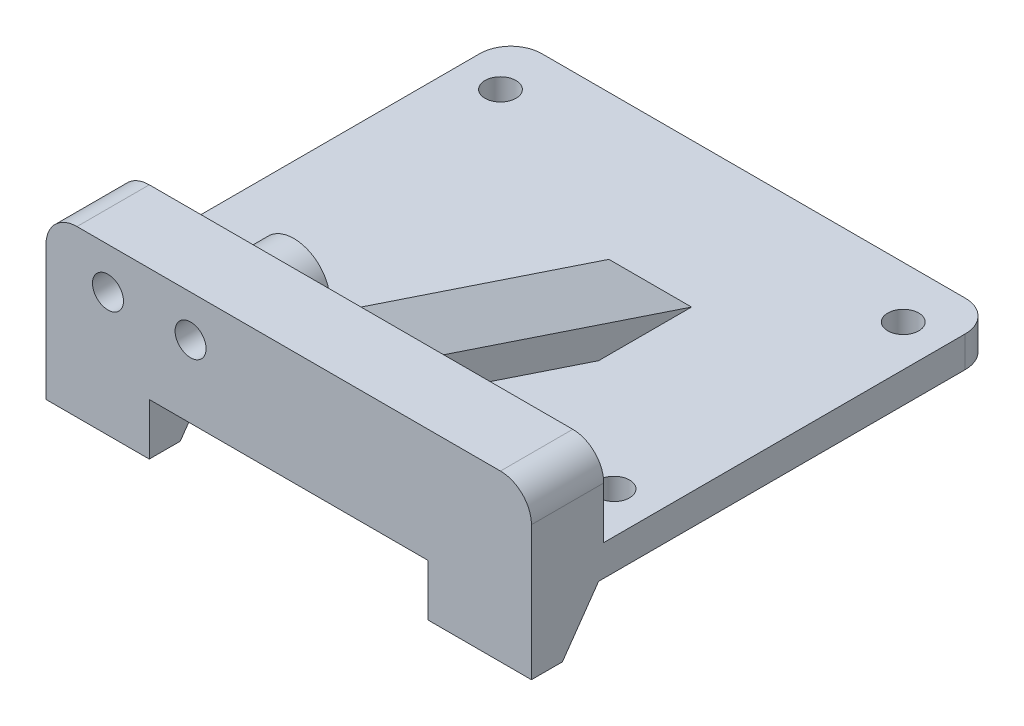
SolidWorks part; units mm, degrees
material "聚脂树脂"
ref_plane "前视基准面" through (0, 0, 0) normal (0, 0, 1) x (1, 0, 0)
ref_plane "上视基准面" through (0, 0, 0) normal (0, 1, 0) x (1, 0, 0)
ref_plane "右视基准面" through (0, 0, 0) normal (1, 0, 0) x (0, 0, -1)
other "Configuration Table"
sketch "草图1" plane through (0, 0, 0) normal (0, 1, 0) x (1, 0, 0)
  line L0 (0, 0) -> (28.4871, 0) construction
  line L1 (-23.5, -19) -> (23.5, -19)
  line L2 (-23.5, -19) -> (-23.5, 19)
  line L3 (-23.5, 19) -> (23.5, 19)
  line L4 (23.5, -19) -> (23.5, 19)
  line L5 (-23.5, -19) -> (23.5, 19) construction
  line L6 (-23.5, 19) -> (23.5, -19) construction
  line L7 (0, 0) -> (0, 25.7908) construction
  circle A0 centre (19.5, 14) radius 1.5
  circle A1 centre (19.5, -14) radius 1.5
  circle A2 centre (-19.5, -14) radius 1.5
  circle A3 centre (-19.5, 14) radius 1.5
  point P0 (0, 0)
  dimension "D1" = 3
  dimension "D2" = 39
  dimension "D3" = 28
  dimension "D4" = 47
  dimension "D5" = 38
extrude "凸台-拉伸1" add sketch "草图1" along normal blind 3
sketch "草图2" plane through (0, 0, 19) normal (0, 0, 1) x (1, 0, 0)
  line L0 (0, 0) -> (0, 15.913) construction
  line L1 (-23.5, 0) -> (-23.5, 11)
  line L2 (-23.5, 11) -> (0, 11)
  line L3 (0, 11) -> (0, 0)
  line L4 (-23.5, 0) -> (23.5, 0) construction
  line L5 (0, 0) -> (-23.5, 0)
  line L8 (23.5, 11) -> (23.5, 0)
  line L10 (23.5, 0) -> (8.5, 0)
  line L11 (8.5, 0) -> (8.5, 11)
  line L12 (8.5, 11) -> (23.5, 11)
  line L13 (0, 11) -> (8.5, 11)
  line L14 (0, 0) -> (8.5, 0)
  circle A0 centre (9.5, 7) radius 1.5
  circle A1 centre (17.5, 7) radius 1.5
  circle A2 centre (-17.5, 7) radius 1.5
  circle A3 centre (-9.5, 7) radius 1.5
  dimension "D4" = 3
  dimension "D5" = 3
  dimension "D6" = 8
  dimension "D9" = 7
  dimension "D10" = 7
  dimension "16.5" = 23.5
  dimension "D2" = 11
  dimension "D3" = 11
  dimension "D7" = 15
  dimension "D8" = 1
  dimension "D11" = 0
extrude "凸台-拉伸2" add sketch "草图2" along normal blind 7
sketch "草图3" plane through (0, 0, 0) normal (1, 0, 0) x (0, 0, -1)
  line L0 (-19, 11) -> (-19, 8)
  line L1 (-19, 11) -> (5, 3)
  line L2 (-19, 3) -> (19, 3) construction
  line L3 (5, 3) -> (-4, 3)
  line L4 (-4, 3) -> (-19, 8)
  dimension "D1" = 3
  dimension "D2" = 9
extrude "凸台-拉伸3" add sketch "草图3" along normal blind 8
fillet "圆角4" radius 3 2 edges at (23.5, 11, 22.5) (-23.5, 11, 22.5)
sketch "草图4" plane through (-23.5, 0, 0) normal (-1, 0, 0) x (0, 0, 1)
  line L0 (26, 0) -> (26, -5)
  line L1 (26, -5) -> (23, -5)
  line L2 (23, -5) -> (19.5, 0)
  line L3 (26, 0) -> (-19, 0) construction
  line L4 (19.5, 0) -> (26, 0)
  dimension "D1" = 6.5
  dimension "D2" = 3
  dimension "D3" = 5
extrude "凸台-拉伸4" add sketch "草图4" against normal blind 10
mirror "镜向1" about plane through (0, 0, 0) normal (1, 0, 0) of "凸台-拉伸4"
sketch "草图6" plane through (23.5, 0, 0) normal (1, 0, 0) x (0, 0, -1)
  line L0 (0, 0) -> (0, 17.1663) construction
  line L1 (0, 0) -> (69.1376, 0) construction
fillet "圆角6" radius 3 2 edges at (23.5, 1.5, -19) (-23.5, 1.5, -19)
sketch "草图7" plane through (0, 0, 19) normal (0, 0, -1) x (-1, 0, 0)
  circle A0 centre (9.5, 7) radius 1.5
  circle A1 centre (9.5, 7) radius 3.5
  dimension "D1" = 3
  dimension "D2" = 7
extrude "凸台-拉伸5" add sketch "草图7" along normal blind 3
